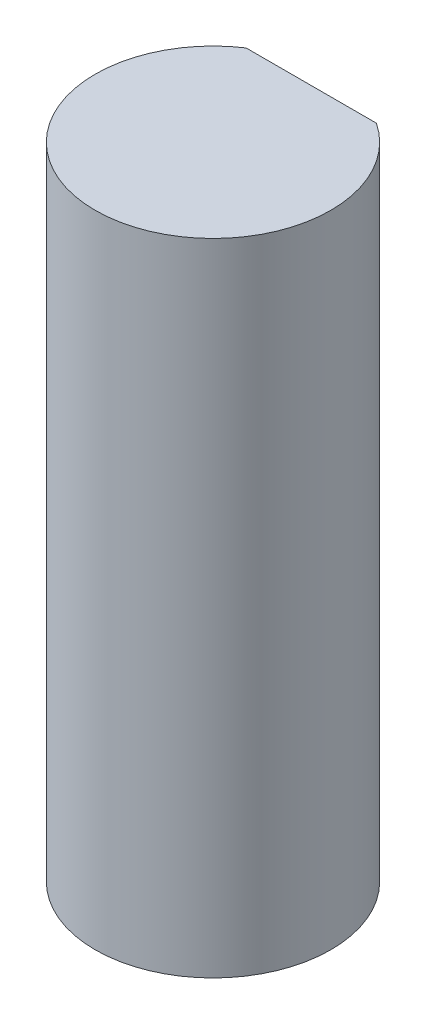
SolidWorks part; units mm, degrees
material "1023 Листовая углеродистая сталь (SS)"
ref_plane "Спереди" through (0, 0, 0) normal (0, 0, 1) x (1, 0, 0)
ref_plane "Сверху" through (0, 0, 0) normal (0, 1, 0) x (1, 0, 0)
ref_plane "Справа" through (0, 0, 0) normal (1, 0, 0) x (0, 0, -1)
sketch "Эскиз1" plane through (0, 0, 0) normal (0, 1, 0) x (1, 0, 0)
  circle A0 centre (0, 0) radius 3
  dimension "D1" = 6
extrude "Бобышка-Вытянуть1" add sketch "Эскиз1" along normal blind 16.3
sketch "Эскиз2" plane through (0, 16.3, 0) normal (0, 1, 0) x (1, 0, 0)
  line L0 (-1.6583, 2.5) -> (1.6583, 2.5)
  arc A0 (1.6583, 2.5) -> (-1.6583, 2.5) centre (0, 0) ccw
  circle A1 centre (0, 0) radius 3 construction
  dimension "D1" = 2.5
extrude "Вырез-Вытянуть1" cut sketch "Эскиз2" against normal blind 12
